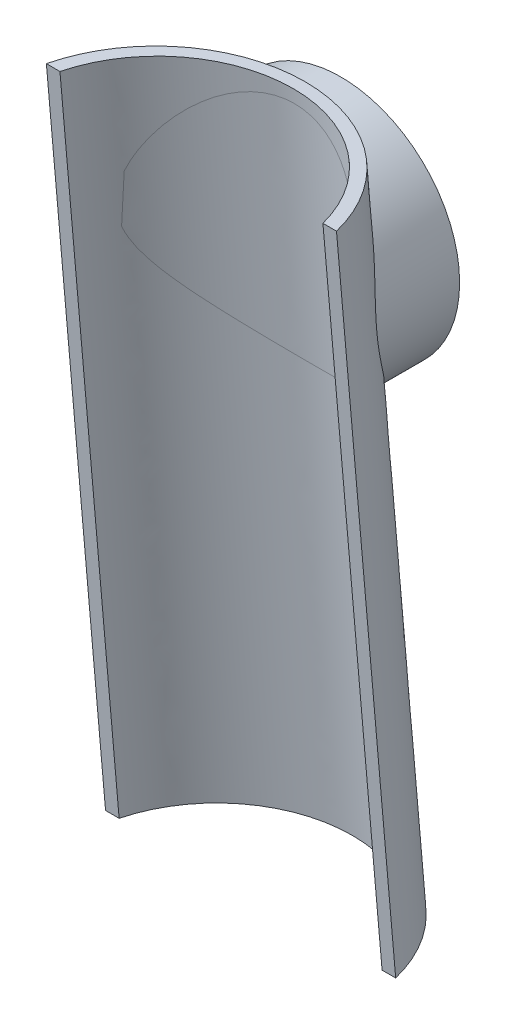
SolidWorks part; units mm, degrees
material "PLA"
ref_plane "Front Plane" through (0, 0, 0) normal (0, 0, 1) x (1, 0, 0)
ref_plane "Top Plane" through (0, 0, 0) normal (0, 1, 0) x (1, 0, 0)
ref_plane "Right Plane" through (0, 0, 0) normal (1, 0, 0) x (0, 0, -1)
sketch "Sketch1" plane through (0, 0, 0) normal (0, 0, 1) x (1, 0, 0)
  circle A1 centre (0, 0) radius 17.5
  dimension "D1" = 35
extrude "Boss-Extrude1" add sketch "Sketch1" along normal blind 15
sketch "Sketch2" plane through (0, 0, 0) normal (0, 0, -1) x (-1, 0, 0)
  line L0 (3, 1.8028) -> (3, 16.1)
  line L1 (-3, -16.1) -> (3, -16.1)
  line L2 (-3, -16.1) -> (-3, -1.8028)
  line L3 (-3, 16.1) -> (3, 16.1)
  line L4 (3, -16.1) -> (3, -1.8028)
  line L5 (-3, -16.1) -> (3, 16.1) construction
  line L6 (-3, 16.1) -> (3, -16.1) construction
  line L7 (-3, 1.8028) -> (-3, 16.1)
  arc A0 (3, -1.8028) -> (3, 1.8028) centre (0, 0) ccw
  arc A1 (-3, 1.8028) -> (-3, -1.8028) centre (0, 0) ccw
  point P0 (0, 0)
  dimension "D1" = 32.2
  dimension "D3" = 7
  dimension "D2" = 6
extrude "Cut-Extrude1" cut sketch "Sketch2" against normal blind 2
ref_plane "Plane1" through (0, 19.5, 0) normal (0, 1, 0) x (1, 0, 0)
sketch "Sketch5" plane through (0, 19.5, 0) normal (0, 1, 0) x (1, 0, 0)
  line L0 (17.5, 0) -> (-17.5, 0) construction
  line L1 (17.5, 0) -> (-17.5, 0) construction
  line L3 (-21.3649, -22) -> (-19.3649, -22)
  line L4 (21.3649, -22) -> (19.3649, -22)
  arc A0 (-19.3649, -22) -> (19.3649, -22) centre (0, -27) cw
  arc A1 (-21.3649, -22) -> (21.3649, -22) centre (0, -27.2479) cw
  point P7 (0, -7)
  point P9 (0, -5.2479)
  dimension "D1" = 20
  dimension "D4" = 22
  dimension "D2" = 7
  dimension "D3" = 15
  dimension "D5" = 2
  dimension "D6" = 2
sketch "Sketch8" plane through (0, 0, 0) normal (1, 0, 0) x (0, 0, -1)
  line L0 (-5.2479, 19.5) -> (3.4677, -80.1195)
  line L2 (0, -17.5) -> (0, 17.5) construction
  line L3 (0, -17.5) -> (0, 17.5) construction
  dimension "D1" = 100
  dimension "D2" = 5
sweep "Sweep1" add profiles "Sketch5" path "Sketch8"
sketch "Sketch9" plane through (0, 19.5, 0) normal (0, 1, 0) x (1, 0, 0)
  circle A0 centre (0, -27) radius 20
extrude "Cut-Extrude2" cut sketch "Sketch9" along direction (0, -0.9962, -0.0872) on the side against the normal up to surface (100 mm away)
